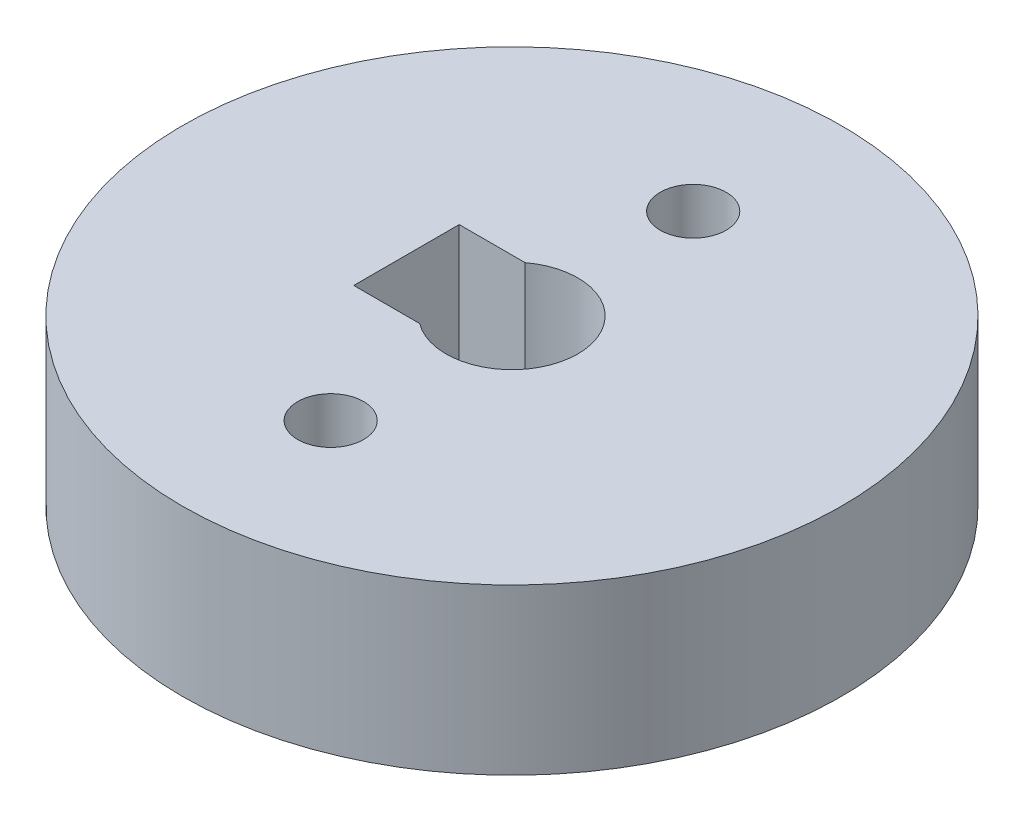
SolidWorks part; units mm, degrees
ref_plane "Front Plane" through (0, 0, 0) normal (0, 0, 1) x (1, 0, 0)
ref_plane "Top Plane" through (0, 0, 0) normal (0, 1, 0) x (1, 0, 0)
ref_plane "Right Plane" through (0, 0, 0) normal (1, 0, 0) x (0, 0, -1)
ref_plane "Plane1"
sketch "Sketch1" plane through (0, 0, 0) normal (0, 1, 0) x (-1, 0, 0)
  line L0 (1.2, 1.6) -> (3.2, 1.6)
  line L1 (3.2, 1.6) -> (3.2, -1.6)
  line L2 (3.2, -1.6) -> (1.2, -1.6)
  circle A0 centre (0, 0) radius 10
  arc A1 (1.2, 1.6) -> (1.2, -1.6) centre (0, 0) ccw
extrude "Extrusion1" add sketch "Sketch1" along normal blind 5 contours A0 A1 L0 L1 L2
hole_wizard "Hole1" positions "Sketch3" profile "Sketch2" legacy end condition through all
sketch "Sketch3" plane through (0, 5, 0) normal (0, 1, 0) x (1, 0, 0)
  point P1 (0, -5.5)
  point P2 (0, 5.5)
sketch "Sketch2" plane through (0, 5, 5.5) normal (1, 0, 0) x (0, 0, 1)
  line L0 (0, 0) -> (0, 5)
  line L1 (0, 5) -> (1, 5)
  line L2 (1, 5) -> (1, 0)
  line L3 (1, 0) -> (0, 0)
  line L4 (0, 110) -> (0, -10) construction
  dimension "Diameter" = 2
  dimension "Depth" = 5
